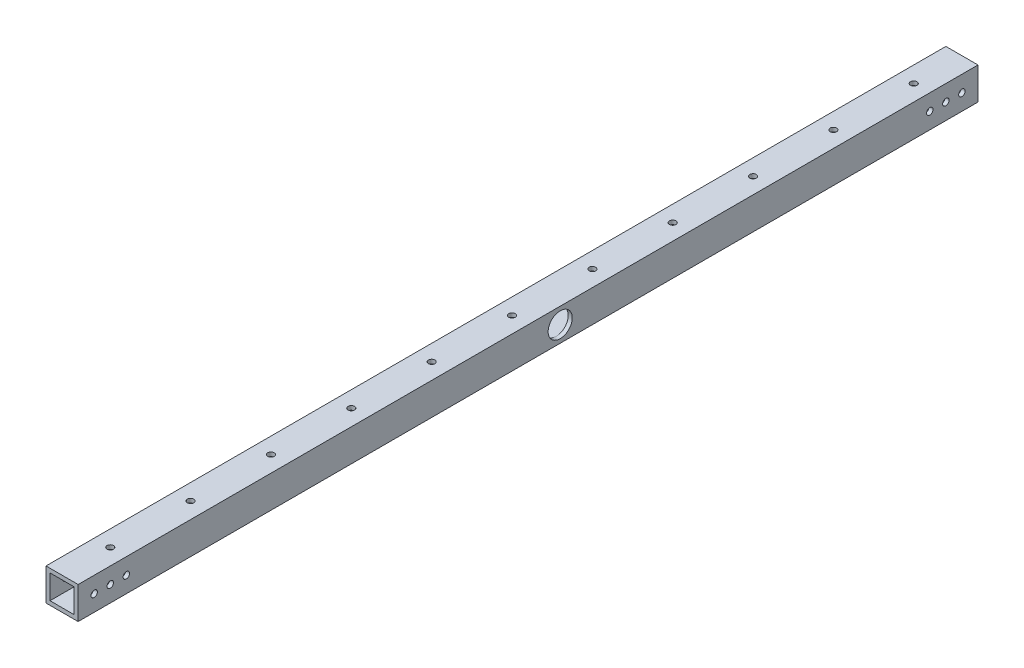
SolidWorks part; units mm, degrees
material "6061 Alloy"
ref_plane "Front" through (0, 0, 0) normal (0, 0, 1) x (1, 0, 0)
ref_plane "Top" through (0, 0, 0) normal (0, 1, 0) x (1, 0, 0)
ref_plane "Right" through (0, 0, 0) normal (1, 0, 0) x (0, 0, -1)
sketch "Sketch1" plane through (0, 0, 0) normal (0, 0, 1) x (1, 0, 0)
  line L1 (0, 0) -> (-25.4, 0)
  line L2 (0, 0) -> (0, 25.4)
  line L3 (0, 25.4) -> (-25.4, 25.4)
  line L4 (-25.4, 0) -> (-25.4, 25.4)
  dimension "D1" = 25.4
  dimension "D2" = 25.4
extrude "Extrude-Thin1" add sketch "Sketch1" along normal blind 711.2 thin
hole_wizard "#10 Clearance Hole1" positions "Sketch2" profile "Sketch3" hole size "#10" standard "ANSI Inch"
sketch "Sketch2" plane through (0, 25.4, 0) normal (0, 1, 0) x (1, 0, 0)
  line L0 (0, -711.2) -> (0, 0) construction
  line L1 (0, -711.2) -> (-25.4, -711.2) construction
  point P0 (-12.7, -673.1)
  dimension "D1" = 12.7
  dimension "D2" = 38.1
sketch "Sketch3" plane through (-12.7, 25.4, 673.1) normal (1, 0, 0) x (0, 0, 1)
  line L0 (0, 0) -> (0, 26.9328)
  line L1 (0, 26.9328) -> (2.5527, 25.399)
  line L2 (2.5527, 25.399) -> (2.5527, 0)
  line L5 (2.5527, 0) -> (0, 0)
  line L10 (0, 26.9328) -> (-2.5527, 25.399) construction
  line L11 (0, -6.35) -> (0, 107.95) construction
  dimension "Hole Dia." = 5.1054
  dimension "Hole Depth" = 25.399
  dimension "Drill Angle" = 118
pattern_linear "LPattern1" count 11 spacing 63.5 along (0, 0, -1) of "#10 Clearance Hole1"
hole_wizard "#10 Clearance Hole2" positions "Sketch4" profile "Sketch5" hole size "#10" standard "ANSI Inch" end condition through all
sketch "Sketch4" plane through (0, 0, 0) normal (1, 0, 0) x (0, 0, -1)
  line L0 (-711.2, 0) -> (-711.2, 25.4) construction
  line L1 (-711.2, 0) -> (0, 0) construction
  point P0 (-698.5, 12.7)
  point P2 (-685.8, 12.7)
  point P12 (-673.1, 12.7)
  dimension "D1" = 12.7
  dimension "D2" = 12.7
  dimension "D3" = 12.7
  dimension "D4" = 12.7
sketch "Sketch5" plane through (0, 12.7, 698.5) normal (0, 1, 0) x (0, 0, -1)
  line L0 (0, 0) -> (0, 25.4)
  line L1 (0, 25.4) -> (2.5527, 25.4)
  line L2 (2.5527, 25.4) -> (2.5527, 0)
  line L5 (2.5527, 0) -> (0, 0)
  line L11 (0, -6.35) -> (0, 107.95) construction
  dimension "Thru Hole Dia." = 5.1054
  dimension "Thru Hole Depth" = 25.4
hole_wizard "#10 Clearance Hole3" positions "Sketch6" profile "Sketch7" hole size "#10" standard "ANSI Inch" end condition through all
sketch "Sketch6" plane through (0, 0, 0) normal (1, 0, 0) x (0, 0, -1)
  line L0 (0, 0) -> (0, 25.4) construction
  line L1 (-711.2, 25.4) -> (0, 25.4) construction
  point P0 (-38.1, 12.7)
  point P2 (-25.4, 12.7)
  point P4 (-12.7, 12.7)
  dimension "D1" = 12.7
  dimension "D2" = 12.7
  dimension "D3" = 12.7
  dimension "D4" = 12.7
sketch "Sketch7" plane through (0, 12.7, 38.1) normal (0, 1, 0) x (0, 0, -1)
  line L0 (0, 0) -> (0, 25.4)
  line L1 (0, 25.4) -> (2.5527, 25.4)
  line L2 (2.5527, 25.4) -> (2.5527, 0)
  line L5 (2.5527, 0) -> (0, 0)
  line L11 (0, -6.35) -> (0, 107.95) construction
  dimension "Thru Hole Dia." = 5.1054
  dimension "Thru Hole Depth" = 25.4
sketch "Sketch8" plane through (-25.4, 0, 0) normal (-1, 0, 0) x (0, 0, 1)
  line L0 (711.2, 25.4) -> (711.2, 0) construction
  line L1 (711.2, 0) -> (0, 0) construction
  circle A0 centre (330.2, 12.7) radius 9.525
  point P4 (0, 0)
  dimension "D1" = 19.05
  dimension "D2" = 381
  dimension "D3" = 12.7
extrude "Cut-Extrude1" cut sketch "Sketch8" against normal through all and the other way through all
